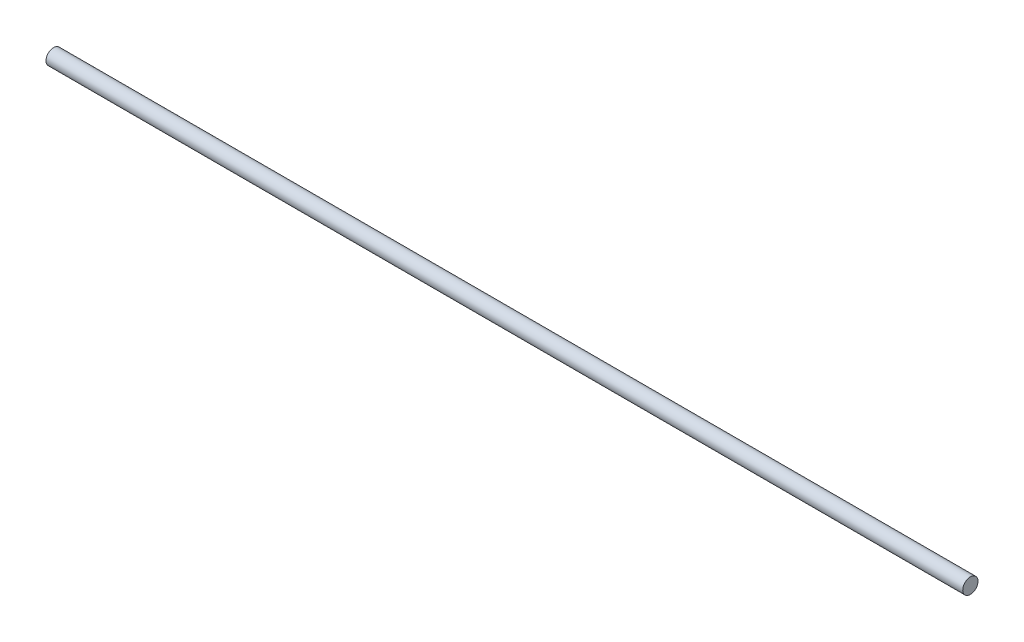
SolidWorks part; units mm, degrees
ref_plane "Front Plane" through (0, 0, 0) normal (0, 0, 1) x (1, 0, 0)
ref_plane "Top Plane" through (0, 0, 0) normal (0, 1, 0) x (1, 0, 0)
ref_plane "Right Plane" through (0, 0, 0) normal (1, 0, 0) x (0, 0, -1)
sketch "Sketch2" plane through (0, 0, 0) normal (1, 0, 0) x (0, 0, -1)
  circle A0 centre (0, 0) radius 1.5
extrude "Boss-Extrude1" add sketch "Sketch2" along normal blind 180
